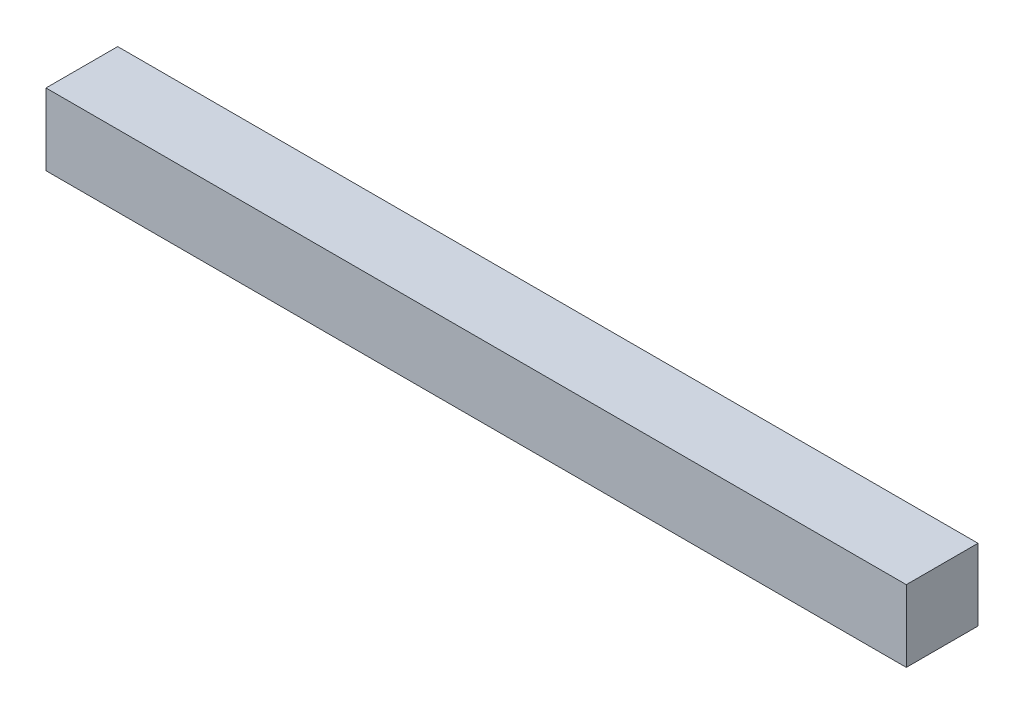
SolidWorks part; units mm, degrees
ref_plane "Front Plane" through (0, 0, 0) normal (0, 0, 1) x (1, 0, 0)
ref_plane "Top Plane" through (0, 0, 0) normal (0, 1, 0) x (1, 0, 0)
ref_plane "Right Plane" through (0, 0, 0) normal (1, 0, 0) x (0, 0, -1)
sketch "Belt Drive Axle" plane through (0, 0, 0) normal (0, 1, 0) x (1, 0, 0)
  line L1 (-38.1, -3.175) -> (38.1, -3.175)
  line L2 (-38.1, -3.175) -> (-38.1, 3.175)
  line L3 (-38.1, 3.175) -> (38.1, 3.175)
  line L4 (38.1, -3.175) -> (38.1, 3.175)
  line L5 (-38.1, -3.175) -> (38.1, 3.175) construction
  line L6 (-38.1, 3.175) -> (38.1, -3.175) construction
  point P0 (0, 0)
  dimension "D1" = 6.35
  dimension "D2" = 76.2
extrude "Boss-Extrude1" add sketch "Belt Drive Axle" along normal blind 6.35
equation "\"Ball Diameter\"= 1.75in"
equation "\"Sheet Thickness\"= 0.25in"
equation "\"Screw Diameter\"= .17in"
equation "\"Robot Diameter\"= 16in"
equation "\"Castor Screw Diameter\"= 0.22in"
equation "\"Wheel Diameter\" = 4in"
equation "\"Nut Diameter\" = 8.4mm"
equation "\"Nut Height\" = 2.9mm"
equation "\"Screw Height\" = 0.55in"
equation "\"Pulley Diameter\" = 1in"
equation "\"Reactor Height\" = 14in"
equation "\"D1@Belt Drive Axle\"=\"Sheet Thickness\""
equation "\"Elevator Height\" = 11.5in"
equation "\"Elevator Width\" = \"Ball Diameter\" + 0.25in"
equation "\"Elevator Axle Length\" = \"Elevator Width\" + 4*\"Sheet Thickness\""
equation "\"D2@Belt Drive Axle\"=\"Elevator Axle Length\""
equation "\"D1@Boss-Extrude1\"=\"Sheet Thickness\""
